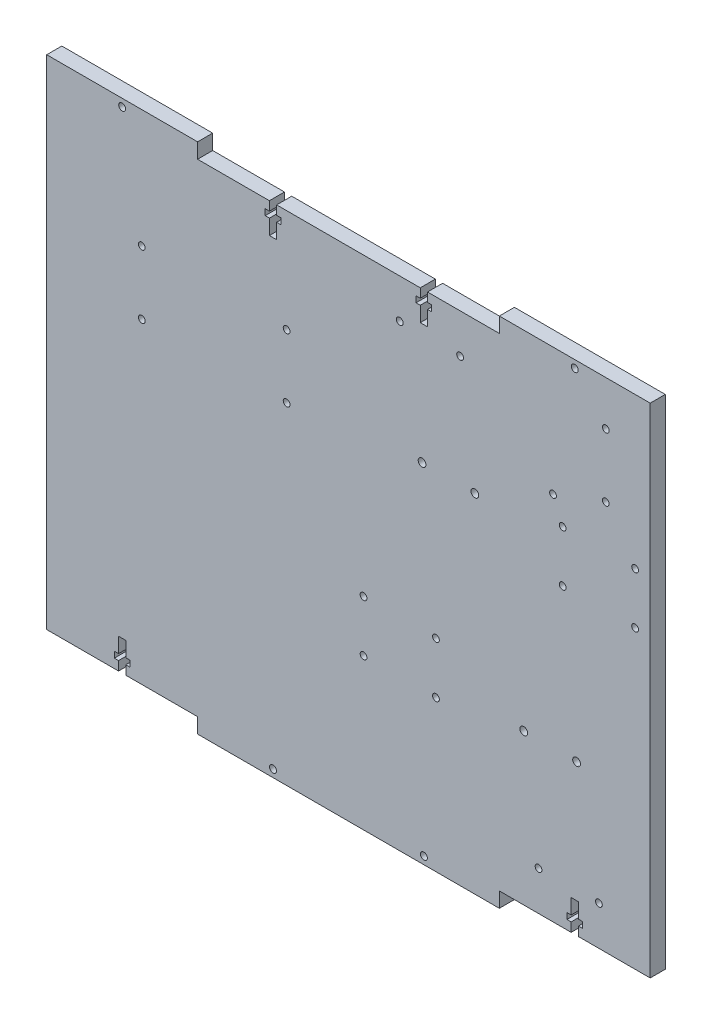
SolidWorks part; units mm, degrees
material "Acrylic (Medium-high impact)"
ref_plane "Front" through (0, 0, 0) normal (0, 0, 1) x (1, 0, 0)
ref_plane "Top" through (0, 0, 0) normal (0, 1, 0) x (1, 0, 0)
ref_plane "Right" through (0, 0, 0) normal (1, 0, 0) x (0, 0, -1)
sketch "Sketch1" plane through (0, 0, 0) normal (0, 0, 1) x (1, 0, 0)
  line L0 (-65.4411, -66.1156) -> (188.5589, -66.1156) construction
  line L5 (-65.4411, 41.8344) -> (188.5589, 41.8344)
  line L6 (-65.4411, 41.8344) -> (-65.4411, -174.0656)
  line L7 (-65.4411, -174.0656) -> (188.5589, -174.0656)
  line L8 (188.5589, 41.8344) -> (188.5589, -174.0656)
  line L9 (-65.4411, 41.8344) -> (125.0589, 41.8344)
  line L10 (-65.4411, 41.8344) -> (-65.4411, 35.4844)
  line L11 (-65.4411, 35.4844) -> (125.0589, 35.4844)
  line L12 (125.0589, 41.8344) -> (125.0589, 35.4844)
  line L13 (61.5589, -167.7156) -> (61.5589, 35.4844) construction
  line L14 (188.5589, -174.0656) -> (125.0589, -174.0656)
  line L15 (-65.4411, -174.0656) -> (-65.4411, -167.7156)
  line L16 (188.5589, -174.0656) -> (188.5589, -167.7156)
  line L17 (188.5589, -167.7156) -> (125.0589, -167.7156)
  line L18 (125.0589, -174.0656) -> (125.0589, -167.7156)
  line L19 (-65.4411, -174.0656) -> (61.5589, -174.0656)
  line L20 (-65.4411, -174.0656) -> (-65.4411, -167.7156)
  line L21 (-65.4411, -167.7156) -> (61.5589, -167.7156)
  line L22 (61.5589, -174.0656) -> (61.5589, -167.7156)
  line L23 (-1.9411, -174.0656) -> (-1.9411, -167.7156)
  line L24 (-1.9411, 41.8344) -> (-1.9411, 35.4844)
  point P9 (-65.4411, -66.1156)
  point P12 (188.5589, -66.1156)
  dimension "D1" = 254
  dimension "D2" = 215.9
  dimension "D3" = 6.35
  dimension "D4" = 0
  dimension "D5" = 63.5
  dimension "D6" = 63.5
  dimension "D7" = 6.35
  dimension "D8" = 63.5
extrude "Boss-Extrude1" add sketch "Sketch1" along normal blind 6.35 contours L22 L7 L18 L17 L8 L5 L12 L11 L6 L21 | L24 L5 L6 L11 | L23 L19 L22 L21
sketch "Sketch3" plane through (0, 0, 6.35) normal (0, 0, 1) x (1, 0, 0)
  line L0 (188.5589, 41.8344) -> (188.5589, -167.7156) construction
  line L1 (-1.9411, -174.0656) -> (125.0589, -174.0656) construction
  line L2 (125.0589, -174.0656) -> (125.0589, -167.7156) construction
  line L4 (125.0589, 41.8344) -> (188.5589, 41.8344) construction
  line L5 (61.5589, 35.4844) -> (61.5589, -174.0656) construction
  line L24 (-1.9411, 35.4844) -> (125.0589, 35.4844) construction
  line L25 (-1.9411, -174.0656) -> (125.0589, -174.0656) construction
  circle A0 centre (156.8089, 38.6594) radius 1.4605
  circle A1 centre (29.8089, -170.8906) radius 1.4605
  circle A2 centre (93.3089, -170.8906) radius 1.4605
  circle A3 centre (-33.6911, 38.6594) radius 1.4605
  dimension "D1" = 2.921
  dimension "D2" = 3.175
  dimension "D12" = 2.921
  dimension "D13" = 3.175
  dimension "D3" = 31.75
  dimension "D14" = 31.75
sketch "Sketch6" plane through (0, 0, 6.35) normal (0, 0, 1) x (1, 0, 0)
  line L0 (-1.9411, 35.4844) -> (125.0589, 35.4844) construction
  line L1 (125.0589, 41.8344) -> (125.0589, 35.4844) construction
  line L2 (188.5589, 41.8344) -> (188.5589, -167.7156) construction
  line L3 (188.5589, -167.7156) -> (125.0589, -167.7156) construction
  circle A0 centre (180.9389, -121.9956) radius 1.524
  circle A1 centre (133.9489, -40.7156) radius 1.524
  circle A2 centre (69.1789, -10.2356) radius 1.524
  circle A3 centre (116.1689, -91.5156) radius 1.524
  point P0 (61.5589, 35.4844)
  dimension "D4" = 3.048
  dimension "D7" = 3.048
  dimension "D10" = 3.048
  dimension "D13" = 3.048
  dimension "D1" = 63.5
  dimension "D2" = 7.62
  dimension "D3" = 45.72
  dimension "D5" = 81.28
  dimension "D6" = 46.99
  dimension "D8" = 7.62
  dimension "D9" = 45.72
  dimension "D11" = 81.28
  dimension "D12" = 46.99
sketch "Sketch7" plane through (0, 0, 6.35) normal (0, 0, 1) x (1, 0, 0)
  circle A0 centre (108.5489, 18.9744) radius 1.4224 construction
  circle A1 centre (83.1489, 18.9744) radius 1.4224 construction
  circle A2 centre (92.5469, -27.8378) radius 1.6319 construction
  circle A3 centre (114.7716, -27.9429) radius 1.6319 construction
  circle A4 centre (67.9089, -88.9756) radius 1.4224 construction
  circle A5 centre (98.3889, -88.9756) radius 1.4224 construction
  circle A6 centre (98.3889, -110.5656) radius 1.4224 construction
  circle A7 centre (67.9089, -110.5656) radius 1.4224 construction
  circle A8 centre (141.5689, -151.2056) radius 1.4224 construction
  circle A9 centre (166.9689, -151.2056) radius 1.4224 construction
  circle A10 centre (135.3461, -104.2882) radius 1.632 construction
  circle A11 centre (157.5709, -104.3934) radius 1.632 construction
  circle A12 centre (151.7289, -43.2556) radius 1.4224 construction
  circle A13 centre (151.7289, -21.6656) radius 1.4224 construction
  circle A14 centre (182.2089, -43.2556) radius 1.4224 construction
  circle A15 centre (182.2089, -21.6656) radius 1.4224 construction
  circle A16 centre (108.5489, 18.9744) radius 1.4224
  circle A17 centre (83.1489, 18.9744) radius 1.4224
  circle A18 centre (92.5469, -27.8378) radius 1.6319
  circle A19 centre (114.7716, -27.9429) radius 1.632
  circle A20 centre (67.9089, -88.9756) radius 1.4224
  circle A21 centre (98.3889, -88.9756) radius 1.4224
  circle A22 centre (98.3889, -110.5656) radius 1.4224
  circle A23 centre (67.9089, -110.5656) radius 1.4224
  circle A24 centre (141.5689, -151.2056) radius 1.4224
  circle A25 centre (166.9689, -151.2056) radius 1.4224
  circle A26 centre (135.3461, -104.2882) radius 1.632
  circle A27 centre (157.5709, -104.3934) radius 1.632
  circle A28 centre (151.7289, -43.2556) radius 1.4224
  circle A29 centre (151.7289, -21.6656) radius 1.4224
  circle A30 centre (182.2089, -43.2556) radius 1.4224
  circle A31 centre (182.2089, -21.6656) radius 1.4224
extrude "Cut-Extrude4" cut sketch "Sketch7" against normal through all
extrude "Cut-Extrude5" cut sketch "Sketch3" against normal through all
sketch "Sketch8" plane through (0, 0, 0) normal (0, 0, -1) x (-1, 0, 0)
  line L0 (1.9411, 35.4844) -> (-125.0589, 35.4844) construction
  line L1 (-91.7849, 35.4844) -> (-94.8329, 35.4844)
  line L2 (-91.7849, 35.4844) -> (-91.7849, 31.6744)
  line L3 (-91.7849, 22.7844) -> (-94.8329, 22.7844)
  line L4 (-94.8329, 35.4844) -> (-94.8329, 31.6744)
  line L5 (-94.8329, 29.1344) -> (-96.6109, 29.1344)
  line L6 (-90.0069, 29.1344) -> (-91.7849, 29.1344)
  line L7 (-90.0069, 29.1344) -> (-90.0069, 31.6744)
  line L8 (-90.0069, 31.6744) -> (-91.7849, 31.6744)
  line L9 (-96.6109, 29.1344) -> (-96.6109, 31.6744)
  line L10 (-91.7849, 29.1344) -> (-91.7849, 22.7844)
  line L11 (-94.8329, 29.1344) -> (-94.8329, 22.7844)
  line L12 (-94.8329, 31.6744) -> (-96.6109, 31.6744)
  line L13 (-125.0589, 41.8344) -> (-125.0589, 35.4844) construction
  line L14 (-61.5589, 35.4844) -> (-61.5589, -174.0656) construction
  line L16 (1.9411, -174.0656) -> (-125.0589, -174.0656) construction
  line L17 (-188.5589, -167.7156) -> (-125.0589, -167.7156) construction
  line L18 (-155.2849, -167.7156) -> (-158.3329, -167.7156)
  line L19 (-155.2849, -167.7156) -> (-155.2849, -163.9056)
  line L20 (-155.2849, -155.0156) -> (-158.3329, -155.0156)
  line L21 (-158.3329, -167.7156) -> (-158.3329, -163.9056)
  line L22 (-158.3329, -163.9056) -> (-160.1109, -163.9056)
  line L23 (-153.5069, -163.9056) -> (-155.2849, -163.9056)
  line L24 (-153.5069, -163.9056) -> (-153.5069, -161.3656)
  line L25 (-153.5069, -161.3656) -> (-155.2849, -161.3656)
  line L26 (-160.1109, -163.9056) -> (-160.1109, -161.3656)
  line L27 (-158.3329, -161.3656) -> (-158.3329, -155.0156)
  line L28 (-158.3329, -161.3656) -> (-160.1109, -161.3656)
  line L29 (-155.2849, -161.3656) -> (-155.2849, -155.0156)
  line L30 (-188.5589, 41.8344) -> (-188.5589, -167.7156) construction
  line L31 (-31.3329, 35.4844) -> (-28.2849, 35.4844)
  line L32 (-28.2849, 35.4844) -> (-28.2849, 31.6744)
  line L33 (-28.2849, 31.6744) -> (-26.5069, 31.6744)
  line L34 (-26.5069, 29.1344) -> (-26.5069, 31.6744)
  line L35 (-28.2849, 29.1344) -> (-26.5069, 29.1344)
  line L36 (-28.2849, 29.1344) -> (-28.2849, 22.7844)
  line L37 (-31.3329, 22.7844) -> (-28.2849, 22.7844)
  line L38 (-31.3329, 29.1344) -> (-31.3329, 22.7844)
  line L39 (-33.1109, 29.1344) -> (-31.3329, 29.1344)
  line L40 (-33.1109, 29.1344) -> (-33.1109, 31.6744)
  line L41 (-33.1109, 31.6744) -> (-31.3329, 31.6744)
  line L42 (-31.3329, 35.4844) -> (-31.3329, 31.6744)
  line L43 (32.1671, -167.7156) -> (32.1671, -163.9056)
  line L44 (32.1671, -167.7156) -> (35.2151, -167.7156)
  line L45 (35.2151, -167.7156) -> (35.2151, -163.9056)
  line L46 (36.9931, -163.9056) -> (36.9931, -161.3656)
  line L47 (35.2151, -161.3656) -> (36.9931, -161.3656)
  line L48 (35.2151, -163.9056) -> (36.9931, -163.9056)
  line L49 (30.3891, -163.9056) -> (32.1671, -163.9056)
  line L50 (30.3891, -163.9056) -> (30.3891, -161.3656)
  line L51 (30.3891, -161.3656) -> (32.1671, -161.3656)
  line L52 (35.2151, -161.3656) -> (35.2151, -155.0156)
  line L53 (32.1671, -155.0156) -> (35.2151, -155.0156)
  line L54 (32.1671, -161.3656) -> (32.1671, -155.0156)
  point P14 (-93.3089, 35.4844)
  point P15 (-95.7219, 29.1344)
  point P21 (-61.5589, -174.0656)
  point P37 (-156.8089, -167.7156)
  dimension "D1" = 12.7
  dimension "D2" = 6.35
  dimension "D3" = 2.54
  dimension "D4" = 6.604
  dimension "D5" = 3.048
  dimension "D6" = 31.75
  dimension "D7" = 12.7
  dimension "D8" = 6.35
  dimension "D9" = 2.54
  dimension "D10" = 3.048
  dimension "D11" = 6.604
  dimension "D12" = 31.75
extrude "Cut-Extrude6" cut sketch "Sketch8" against normal through all
sketch "Sketch10" plane through (0, 0, 6.35) normal (0, 0, 1) x (1, 0, 0)
  line L0 (188.5589, 41.8344) -> (188.5589, -167.7156) construction
  line L1 (125.0589, 41.8344) -> (188.5589, 41.8344) construction
  circle A0 centre (169.8899, -3.5756) radius 1.4224
  circle A1 centre (169.8899, 23.0944) radius 1.4224
  circle A2 centre (147.6649, -11.8306) radius 1.4224
  dimension "D1" = 2.8448
  dimension "D2" = 2.8448
  dimension "D3" = 2.8448
  dimension "D4" = 18.669
  dimension "D5" = 18.74
  dimension "D6" = 18.669
  dimension "D7" = 26.67
  dimension "D8" = 53.665
  dimension "D9" = 40.894
extrude "Cut-Extrude7" cut sketch "Sketch10" against normal through all
sketch "Sketch11" plane through (0, 0, 6.35) normal (0, 0, 1) x (1, 0, 0)
  line L0 (-1.9411, 35.4844) -> (28.2849, 35.4844) construction
  line L1 (-65.4411, 41.8344) -> (-65.4411, -167.7156) construction
  line L2 (31.3329, 35.4844) -> (91.7849, 35.4844) construction
  line L3 (-65.4411, 41.8344) -> (-1.9411, 41.8344) construction
  circle A0 centre (-25.4288, -7.9056) radius 1.4224
  circle A1 centre (-25.4288, -34.5756) radius 1.4224
  circle A2 centre (35.5312, -34.5756) radius 1.4224
  circle A3 centre (35.5312, -7.9056) radius 1.4224
  dimension "D1" = 2.8448
  dimension "D2" = 70.06
  dimension "D3" = 100.9723
  dimension "D4" = 43.39
  dimension "D5" = 100.9723
  dimension "D6" = 49.74
  dimension "D7" = 40.0123
  dimension "D8" = 76.41
  dimension "D9" = 40.0123
extrude "Cut-Extrude8" cut sketch "Sketch11" against normal through all
